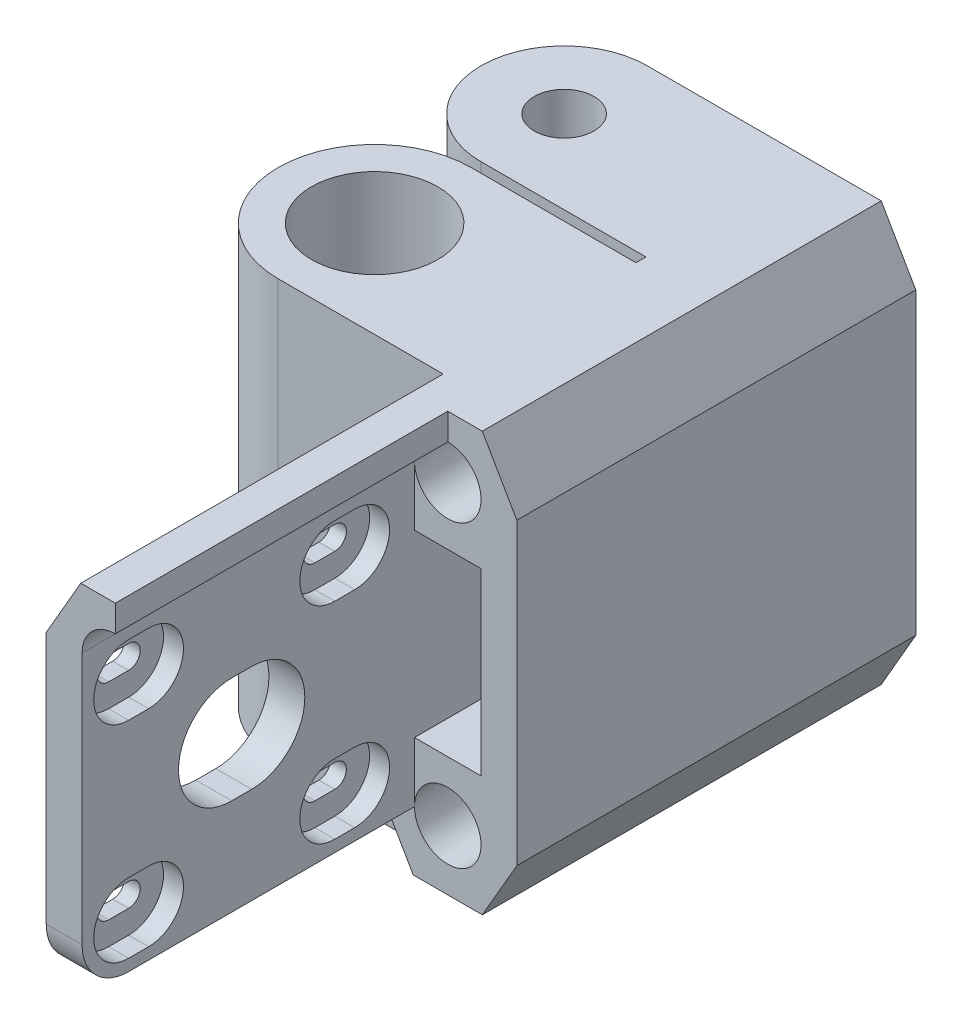
SolidWorks part; units mm, degrees
ref_plane "Front Plane" through (0, 0, 0) normal (0, 0, 1) x (1, 0, 0)
ref_plane "Top Plane" through (0, 0, 0) normal (0, 1, 0) x (1, 0, 0)
ref_plane "Right Plane" through (0, 0, 0) normal (1, 0, 0) x (0, 0, -1)
sketch "Sketch1" plane through (0, 0, 0) normal (0, 0, 1) x (1, 0, 0)
  line L0 (-10.3923, 22.5) -> (-10.3923, -22.5)
  line L1 (10.3923, 22.5) -> (5.1962, 31.5)
  line L2 (5.1962, 31.5) -> (-5.1962, 31.5)
  line L3 (-5.1962, 31.5) -> (-10.3923, 22.5)
  line L5 (-5, 13.5) -> (5, 13.5)
  line L8 (5, -13.5) -> (-5, -13.5)
  line L10 (-10.3923, -22.5) -> (-5.1962, -31.5)
  line L11 (-5.1962, -31.5) -> (5.1962, -31.5)
  line L12 (5.1962, -31.5) -> (10.3923, -22.5)
  line L13 (-5, 13.5) -> (-5, -13.5)
  line L14 (5, 13.5) -> (5, -13.5)
  line L15 (10.3923, 22.5) -> (10.3923, -22.5)
  line L17 (7.7942, 18) -> (10.3923, 22.5) [skipped]
  line L18 (-10.3923, 22.5) -> (-7.7942, 18) [skipped]
  line L19 (-7.7942, -18) -> (-10.3923, -22.5) [skipped]
  line L20 (10.3923, -22.5) -> (7.7942, -18) [skipped]
  circle A0 centre (0, 22.5) radius 5
  circle A1 centre (0, -22.5) radius 5
  circle A2 centre (0, 22.5) radius 9 construction
  circle A3 centre (0, -22.5) radius 9 construction
  dimension "D1" = 45
  dimension "D3" = 10
  dimension "D4" = 4
  dimension "D2" = 22.5
  dimension "D5" = 10
  dimension "D6" = 5
extrude "Boss-Extrude1" add sketch "Sketch1" along normal blind 60
sketch "Sketch2" plane through (0, 31.5, 0) normal (0, -1, 0) x (1, 0, 0)
  line L1 (-10.3923, 0) -> (-5.1962, 0) construction
  line L2 (-5.1962, 0) -> (5.1962, 0) construction
  line L3 (-30, 25) -> (-5.1962, 25)
  line L4 (-5.1962, 60) -> (-5.1962, 0) construction
  line L5 (-5.1962, 25) -> (-5.1962, 0)
  line L6 (-5.1962, 0) -> (-30, 0)
  circle A0 centre (-30, 12.5) radius 4.5
  arc A1 (-30, 25) -> (-30, 0) centre (-30, 12.5) ccw
  dimension "D1" = 9
  dimension "D4" = 8
  dimension "D2" = 30
  dimension "D3" = 0
  dimension "D5" = 12.5
extrude "Boss-Extrude2" add sketch "Sketch2" along normal up to surface (18 mm away) up to face at (0, 13.5, 30)
sketch "Sketch3" plane through (0, 13.5, 0) normal (0, -1, 0) x (-1, 0, 0)
  line L1 (33.7528, -6) -> (26.2472, -6)
  line L2 (26.2472, -6) -> (22.4944, -12.5)
  line L3 (22.4944, -12.5) -> (26.2472, -19)
  line L4 (26.2472, -19) -> (33.7528, -19)
  line L5 (33.7528, -19) -> (37.5056, -12.5)
  line L6 (37.5056, -12.5) -> (33.7528, -6)
  circle A0 centre (30, -12.5) radius 6.5 construction
  dimension "D1" = 13
extrude "Cut-Extrude1" cut sketch "Sketch3" against normal blind 7
sketch "Sketch4" plane through (0, -31.5, 0) normal (0, -1, 0) x (1, 0, 0)
  line L0 (-30, 12.5) -> (-30, 41) construction
  line L1 (-30, 55.5) -> (-5.1962, 55.5)
  line L2 (-5.1962, 60) -> (-5.1962, 0) construction
  line L3 (-5.1962, 55.5) -> (-5.1962, 26.5)
  line L4 (-5.1962, 26.5) -> (-30, 26.5)
  circle A0 centre (-30, 41) radius 9.5
  arc A1 (-30, 55.5) -> (-30, 26.5) centre (-30, 41) ccw
  dimension "D1" = 19
  dimension "D2" = 5
  dimension "D3" = 28.5
extrude "Boss-Extrude3" add sketch "Sketch4" against normal up to surface (63 mm away)
sketch "Sketch34" plane through (0, 0, 60) normal (0, 0, 1) x (1, 0, 0)
  line L1 (-10.3923, 22.5) -> (-10.3923, -22.5)
  line L7 (-5, 22.5) -> (-5, -22.5)
  line L8 (-10.3923, 22.5) -> (-5.1962, 31.5)
  line L9 (-5.1962, 31.5) -> (0, 31.5)
  line L10 (5.1962, 31.5) -> (-5.1962, 31.5) construction
  line L11 (0, 31.5) -> (0, 27.5)
  line L12 (-5, -22.5) -> (-10.3923, -22.5)
  circle A0 centre (0, 22.5) radius 5 construction
  circle A1 centre (0, -22.5) radius 5 construction
  arc A3 (0, 27.5) -> (-5, 22.5) centre (0, 22.5) ccw
extrude "Boss-Extrude5" add sketch "Sketch34" along normal blind 50
sketch "Sketch26" plane through (-5, -6.617, 13.0783) normal (1, 0, 0) x (0, 0, -1)
  line L0 (-52.9217, -14.883) -> (-95.9217, 28.117) construction
  line L1 (-52.9217, -14.883) -> (-95.9217, -14.883) construction
  line L2 (-52.9217, -14.883) -> (-52.9217, 28.117) construction
  line L3 (-52.9217, 28.117) -> (-95.9217, 28.117) construction
  line L4 (-95.9217, -14.883) -> (-95.9217, 28.117) construction
  line L5 (-95.9217, -14.883) -> (-52.9217, 28.117) construction
  line L6 (-89.9217, 22.117) -> (-86.9217, 22.117) construction
  line L7 (-89.9217, 23.867) -> (-86.9217, 23.867)
  line L8 (-89.9217, 20.367) -> (-86.9217, 20.367)
  line L9 (-58.9217, 22.117) -> (-55.9217, 22.117) construction
  line L10 (-58.9217, 23.867) -> (-55.9217, 23.867)
  line L11 (-58.9217, 20.367) -> (-55.9217, 20.367)
  line L12 (-58.9217, -8.883) -> (-55.9217, -8.883) construction
  line L13 (-58.9217, -7.133) -> (-55.9217, -7.133)
  line L14 (-58.9217, -10.633) -> (-55.9217, -10.633)
  line L15 (-89.9217, -8.883) -> (-86.9217, -8.883) construction
  line L16 (-89.9217, -7.133) -> (-86.9217, -7.133)
  line L17 (-89.9217, -10.633) -> (-86.9217, -10.633)
  line L18 (-74.4217, 6.617) -> (-71.4217, 6.617) construction
  line L19 (-74.4217, 14.617) -> (-71.4217, 14.617)
  line L20 (-74.4217, -1.383) -> (-71.4217, -1.383)
  line L21 (-96.9217, -15.883) -> (-46.9217, -15.883) construction
  line L22 (-96.9217, 29.117) -> (-96.9217, -15.883) construction
  arc A0 (-89.9217, 23.867) -> (-89.9217, 20.367) centre (-89.9217, 22.117) ccw
  arc A1 (-86.9217, 20.367) -> (-86.9217, 23.867) centre (-86.9217, 22.117) ccw
  arc A2 (-58.9217, 23.867) -> (-58.9217, 20.367) centre (-58.9217, 22.117) ccw
  arc A3 (-55.9217, 20.367) -> (-55.9217, 23.867) centre (-55.9217, 22.117) ccw
  arc A4 (-58.9217, -7.133) -> (-58.9217, -10.633) centre (-58.9217, -8.883) ccw
  arc A5 (-55.9217, -10.633) -> (-55.9217, -7.133) centre (-55.9217, -8.883) ccw
  arc A6 (-89.9217, -7.133) -> (-89.9217, -10.633) centre (-89.9217, -8.883) ccw
  arc A7 (-86.9217, -10.633) -> (-86.9217, -7.133) centre (-86.9217, -8.883) ccw
  arc A8 (-74.4217, 14.617) -> (-74.4217, -1.383) centre (-74.4217, 6.617) ccw
  arc A9 (-71.4217, -1.383) -> (-71.4217, 14.617) centre (-71.4217, 6.617) ccw
  point P6 (-88.4217, 22.117)
  point P11 (-57.4217, 22.117)
  point P18 (-57.4217, -8.883)
  point P25 (-88.4217, -8.883)
  point P34 (-72.9217, 6.617)
  dimension "D2" = 1.75
  dimension "D4" = 8
  dimension "D1" = 3
  dimension "D3" = 3
  dimension "D5" = 31
  dimension "D6" = 43
  dimension "D7" = 1
  dimension "D8" = 44
extrude "Cut-Extrude16" cut sketch "Sketch26" against normal blind 20
sketch "Sketch37" plane through (-5, 8.4948, 122.051) normal (1, 0, 0) x (0, 0, -1)
  line L0 (22.051, 8.7552) -> (19.051, 8.7552) construction
  line L1 (19.051, 5.2552) -> (22.051, 5.2552) construction
  line L2 (53.051, 8.7552) -> (50.051, 8.7552) construction
  line L3 (50.051, 5.2552) -> (53.051, 5.2552) construction
  line L4 (53.051, -22.2448) -> (50.051, -22.2448) construction
  line L5 (50.051, -25.7448) -> (53.051, -25.7448) construction
  line L6 (19.051, -25.7448) -> (22.051, -25.7448) construction
  line L7 (22.051, -22.2448) -> (19.051, -22.2448) construction
  line L8 (22.051, 8.7552) -> (19.051, 8.7552) construction
  line L9 (19.051, 5.2552) -> (22.051, 5.2552) construction
  line L10 (53.051, 8.7552) -> (50.051, 8.7552) construction
  line L11 (50.051, 5.2552) -> (53.051, 5.2552) construction
  line L12 (53.051, -22.2448) -> (50.051, -22.2448) construction
  line L13 (50.051, -25.7448) -> (53.051, -25.7448) construction
  line L14 (19.051, -25.7448) -> (22.051, -25.7448) construction
  line L15 (22.051, -22.2448) -> (19.051, -22.2448) construction
  line L16 (22.051, 12.2552) -> (19.051, 12.2552)
  line L17 (19.051, 1.7552) -> (22.051, 1.7552)
  line L18 (53.051, 12.2552) -> (50.051, 12.2552)
  line L19 (50.051, 1.7552) -> (53.051, 1.7552)
  line L20 (53.051, -18.7448) -> (50.051, -18.7448)
  line L21 (50.051, -29.2448) -> (53.051, -29.2448)
  line L22 (19.051, -29.2448) -> (22.051, -29.2448)
  line L23 (22.051, -18.7448) -> (19.051, -18.7448)
  arc A0 (19.051, 8.7552) -> (19.051, 5.2552) centre (19.051, 7.0052) ccw construction
  arc A1 (22.051, 5.2552) -> (22.051, 8.7552) centre (22.051, 7.0052) ccw construction
  arc A2 (50.051, 8.7552) -> (50.051, 5.2552) centre (50.051, 7.0052) ccw construction
  arc A3 (53.051, 5.2552) -> (53.051, 8.7552) centre (53.051, 7.0052) ccw construction
  arc A4 (53.051, -25.7448) -> (53.051, -22.2448) centre (53.051, -23.9948) ccw construction
  arc A5 (50.051, -22.2448) -> (50.051, -25.7448) centre (50.051, -23.9948) ccw construction
  arc A6 (22.051, -25.7448) -> (22.051, -22.2448) centre (22.051, -23.9948) ccw construction
  arc A7 (19.051, -22.2448) -> (19.051, -25.7448) centre (19.051, -23.9948) ccw construction
  arc A8 (19.051, 8.7552) -> (19.051, 5.2552) centre (19.051, 7.0052) ccw construction
  arc A9 (22.051, 5.2552) -> (22.051, 8.7552) centre (22.051, 7.0052) ccw construction
  arc A10 (50.051, 8.7552) -> (50.051, 5.2552) centre (50.051, 7.0052) ccw construction
  arc A11 (53.051, 5.2552) -> (53.051, 8.7552) centre (53.051, 7.0052) ccw construction
  arc A12 (53.051, -25.7448) -> (53.051, -22.2448) centre (53.051, -23.9948) ccw construction
  arc A13 (50.051, -22.2448) -> (50.051, -25.7448) centre (50.051, -23.9948) ccw construction
  arc A14 (22.051, -25.7448) -> (22.051, -22.2448) centre (22.051, -23.9948) ccw construction
  arc A15 (19.051, -22.2448) -> (19.051, -25.7448) centre (19.051, -23.9948) ccw construction
  arc A16 (19.051, 12.2552) -> (19.051, 1.7552) centre (19.051, 7.0052) ccw
  arc A17 (22.051, 1.7552) -> (22.051, 12.2552) centre (22.051, 7.0052) ccw
  arc A18 (50.051, 12.2552) -> (50.051, 1.7552) centre (50.051, 7.0052) ccw
  arc A19 (53.051, 1.7552) -> (53.051, 12.2552) centre (53.051, 7.0052) ccw
  arc A20 (50.051, -18.7448) -> (50.051, -29.2448) centre (50.051, -23.9948) ccw
  arc A21 (53.051, -29.2448) -> (53.051, -18.7448) centre (53.051, -23.9948) ccw
  arc A22 (22.051, -29.2448) -> (22.051, -18.7448) centre (22.051, -23.9948) ccw
  arc A23 (19.051, -18.7448) -> (19.051, -29.2448) centre (19.051, -23.9948) ccw
  dimension "D1" = 3.5
extrude "Cut-Extrude2" cut sketch "Sketch37" against normal blind 3
other "nema17slots<1>"
fillet "Fillet1" radius 7 1 edges at (-7.6962, -22.5, 110)
